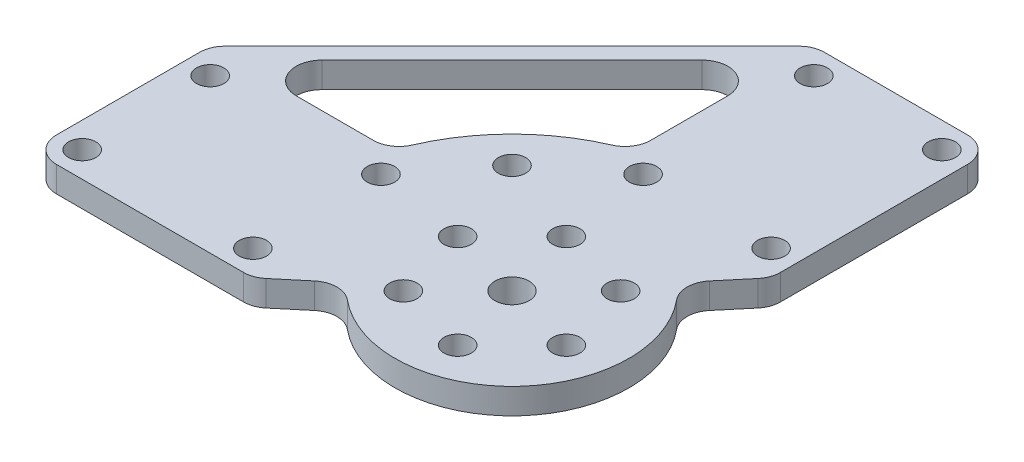
SolidWorks part; units mm, degrees
material "6061-T6 (SS)"
ref_plane "Front Plane" through (0, 0, 0) normal (0, 0, 1) x (1, 0, 0)
ref_plane "Top Plane" through (0, 0, 0) normal (0, 1, 0) x (1, 0, 0)
ref_plane "Right Plane" through (0, 0, 0) normal (1, 0, 0) x (0, 0, -1)
sketch "Sketch1" plane through (0, 0, 0) normal (0, 1, 0) x (1, 0, 0)
  line L0 (-14.5, -32) -> (14.5, -32) construction
  line L1 (10.85, 19.5) -> (-4.15, 19.5)
  line L2 (10.85, 19.5) -> (10.85, 39.5)
  line L3 (10.85, 39.5) -> (-4.15, 39.5)
  line L4 (-4.15, 19.5) -> (-4.15, 39.5)
  line L5 (10.85, 19.5) -> (-4.15, 39.5) construction
  line L6 (10.85, 39.5) -> (-4.15, 19.5) construction
  line L7 (-19.5, -10.85) -> (-39.5, -10.85)
  line L8 (-19.5, -10.85) -> (-19.5, 4.15)
  line L9 (-19.5, 4.15) -> (-39.5, 4.15)
  line L10 (-39.5, -10.85) -> (-39.5, 4.15)
  line L11 (-19.5, -10.85) -> (-39.5, 4.15) construction
  line L12 (-19.5, 4.15) -> (-39.5, -10.85) construction
  line L13 (20.7, 16) -> (-14, 16)
  line L14 (20.7, 16) -> (20.7, 43)
  line L15 (20.7, 43) -> (-14, 43)
  line L16 (-14, 16) -> (-14, 43)
  line L17 (20.7, 16) -> (-14, 43) construction
  line L18 (20.7, 43) -> (-14, 16) construction
  line L19 (-16, -20.7) -> (-43, -20.7)
  line L20 (-16, -20.7) -> (-16, 14)
  line L21 (-16, 14) -> (-43, 14)
  line L22 (-43, -20.7) -> (-43, 14)
  line L23 (-16, -20.7) -> (-43, 14) construction
  line L24 (-16, 14) -> (-43, -20.7) construction
  line L25 (10, -37) -> (-10, -37)
  line L26 (10, -37) -> (10, -27)
  line L27 (10, -27) -> (-10, -27)
  line L28 (-10, -37) -> (-10, -27)
  line L29 (10, -37) -> (-10, -27) construction
  line L30 (10, -27) -> (-10, -37) construction
  line L31 (37, -10) -> (27, -10)
  line L32 (37, -10) -> (37, 10)
  line L33 (37, 10) -> (27, 10)
  line L34 (27, -10) -> (27, 10)
  line L35 (37, -10) -> (27, 10) construction
  line L36 (37, 10) -> (27, -10) construction
  line L37 (32, 14.5) -> (32, -14.5) construction
  circle A0 centre (0, 0) radius 2
  circle A1 centre (0, 0) radius 9
  circle A2 centre (0, 0) radius 12.7
  point P3 (3.35, 29.5)
  point P8 (-29.5, -3.35)
  point P15 (0, -32)
  point P16 (-29.5, -3.35)
  point P17 (3.35, 29.5)
  point P30 (32, 0)
  point P38 (0, -32)
  point P41 (32, 0)
  dimension "D1" = 4
  dimension "D4" = 18
  dimension "D11" = 25.4
  dimension "D2" = 20
  dimension "D3" = 15
  dimension "D5" = 34.7
  dimension "D6" = 27
  dimension "D7" = 2
  dimension "D8" = 2
  dimension "D9" = 16
  dimension "D10" = 16
  dimension "D12" = 32
  dimension "D13" = 10
  dimension "D14" = 20
  dimension "D15" = 32
  dimension "D16" = 4.5
sketch "Sketch2" plane through (0, 0, 0) normal (0, 1, 0) x (1, 0, 0)
  line L3 (-16.5, -13.85) -> (-42.5, -13.85)
  line L4 (-42.5, -13.85) -> (-42.5, 7.15)
  line L5 (-42.5, 7.15) -> (-24.825, 24.825)
  line L6 (-19.5, -10.85) -> (-39.5, -10.85) construction
  line L9 (-39.5, -10.85) -> (-39.5, 4.15) construction
  line L10 (-19.5, -10.85) -> (-19.5, 4.15) construction
  line L12 (-19.5, 4.15) -> (-39.5, 4.15) construction
  line L16 (-16.5, -13.85) -> (-16.5, -29.1277)
  line L22 (16.9749, -34.4749) -> (25.7249, -25.7249)
  line L29 (25.7249, -25.7249) -> (-24.825, 24.825)
  line L39 (12, -27) -> (12, -39)
  line L40 (12, -39) -> (-12, -39)
  line L41 (-12, -39) -> (-12, -27)
  line L42 (12, -34.4495) -> (12, -39)
  line L43 (12, -39) -> (-12, -39)
  line L44 (-12, -39) -> (-12, -34.4495)
  arc A0 (-16.5, -29.1277) -> (-12, -34.4495) centre (-14.5, -32) ccw
  arc A2 (12, -34.4495) -> (16.9749, -34.4749) centre (14.5, -32) ccw
  dimension "D1" = 7
  dimension "D2" = 3
  dimension "D3" = 45
  dimension "D4" = 2
  dimension "D5" = 3
  dimension "D6" = 3
  dimension "D8" = 3
extrude "Boss-Extrude1" add sketch "Sketch2" along normal blind 3
mirror "Mirror5" about plane through (25.7249, 3, 25.7249) normal (-0.7071, 0, 0.7071) of bodies 101
hole_wizard "M3 Clearance Hole1" positions "Sketch3" profile "Sketch4" hole size "M3" standard "ANSI Metric" end condition up to next
sketch "Sketch3" plane through (0, 3, 0) normal (0, 1, 0) x (1, 0, 0)
  point P0 (-39.5, 4.15)
  point P3 (-19.5, 4.15)
  point P6 (-19.5, -10.85)
  point P9 (-39.5, -10.85)
  point P12 (-4.15, 19.5)
  point P15 (-4.15, 39.5)
  point P18 (10.85, 39.5)
  point P21 (10.85, 19.5)
sketch "Sketch4" plane through (-39.5, 3, -4.15) normal (1, 0, 0) x (0, 0, 1)
  line L0 (0, 0) -> (0, 3)
  line L1 (0, 3) -> (1.6, 3)
  line L2 (1.6, 3) -> (1.6, 0)
  line L5 (1.6, 0) -> (0, 0)
  line L11 (0, -6.35) -> (0, 107.95) construction
  dimension "Thru Hole Dia." = 3.2
  dimension "Thru Hole Depth" = 3
hole_wizard "M3 Clearance Hole2" positions "Sketch5" profile "Sketch6" hole size "M3" standard "ANSI Metric" end condition up to next
sketch "Sketch5" plane through (0, 3, 0) normal (0, 1, 0) x (1, 0, 0)
  line L4 (-8.6933, 2.3294) -> (-2.3294, 8.6933) construction
  line L5 (0, 0) -> (-5.5114, 5.5114) construction
  line L7 (-1000, 0) -> (49000, 0) construction
  circle A0 centre (0, 0) radius 9 construction
  point P23 (-2.3294, 8.6933)
  point P46 (6.364, 6.364)
  point P47 (8.6933, -2.3294)
  point P48 (2.3294, -8.6933)
  point P49 (-6.364, -6.364)
  point P50 (-8.6933, 2.3294)
  dimension "D1" = 45
  dimension "D2" = 6
sketch "Sketch6" plane through (-2.3294, 3, -8.6933) normal (1, 0, 0) x (0, 0, 1)
  line L0 (0, 0) -> (0, 3)
  line L1 (0, 3) -> (1.6, 3)
  line L2 (1.6, 3) -> (1.6, 0)
  line L5 (1.6, 0) -> (0, 0)
  line L11 (0, -6.35) -> (0, 107.95) construction
  dimension "Thru Hole Dia." = 3.2
  dimension "Thru Hole Depth" = 3
hole_wizard "Ø4.0 (4) Diameter Hole1" positions "Sketch7" profile "Sketch8" hole size "Ø4.0" standard "ANSI Metric" end condition up to next
sketch "Sketch7" plane through (0, 3, 0) normal (0, 1, 0) x (1, 0, 0)
  point P0 (0, 0)
sketch "Sketch8" plane through (0, 3, 0) normal (1, 0, 0) x (0, 0, 1)
  line L0 (0, 0) -> (0, 3)
  line L1 (0, 3) -> (2, 3)
  line L2 (2, 3) -> (2, 0)
  line L5 (2, 0) -> (0, 0)
  line L11 (0, -6.35) -> (0, 107.95) construction
  dimension "Thru Hole Dia." = 4
  dimension "Thru Hole Depth" = 3
sketch "Sketch13" plane through (0, 3, 0) normal (0, 1, 0) x (1, 0, 0)
  line L0 (-39.6716, 7.15) -> (-21.3337, 7.15)
  line L1 (0, 0) -> (-24.825, 24.825) construction
  line L2 (-7.15, 42.5) -> (-42.5, 7.15) construction
  line L4 (-23.4108, 23.4108) -> (-15.9099, 15.9099)
  line L5 (-5.7358, 41.0858) -> (-41.0858, 5.7358)
  line L6 (-23.4108, 23.4108) -> (-39.6716, 7.15)
  circle A2 centre (0, 0) radius 22.5 construction
  circle A3 centre (-19.5, 4.15) radius 1.6 construction
  arc A4 (-21.3337, 7.15) -> (-15.9099, 15.9099) centre (0, 0) cw
  dimension "D1" = 45
  dimension "D2" = 3
  dimension "D3" = 2
extrude "Cut-Extrude3" cut sketch "Sketch13" against normal up to surface (3 mm away) contours L0 A4 L4 L6 up to face at (0, 0, 2)
mirror "Mirror6" about plane through (0, -28.7929, 0) normal (-0.7071, 0, 0.7071) of "Cut-Extrude3"
fillet "Fillet5" radius 3 4 edges at (-7.15, 1.5, -39.6716) (-7.15, 1.5, -21.3337) (-21.3337, 1.5, -7.15) (-39.6716, 1.5, -7.15)
hole_wizard "M3 Clearance Hole3" positions "Sketch14" profile "Sketch15" hole size "M3" standard "ANSI Metric" end condition up to next
sketch "Sketch14" plane through (0, 3, 0) normal (0, 1, 0) x (1, 0, 0)
  line L0 (-12.7279, 12.7279) -> (0, 0) construction
  line L2 (-12.2713, 34.5503) -> (-34.5503, 12.2713) construction
  circle A2 centre (-12.7279, 12.7279) radius 3
  point P0 (-12.7279, 12.7279)
  dimension "D1" = 6
  dimension "D2" = 18
sketch "Sketch15" plane through (-12.7279, 3, -12.7279) normal (1, 0, 0) x (0, 0, 1)
  line L0 (0, 0) -> (0, 3)
  line L1 (0, 3) -> (1.6, 3)
  line L2 (1.6, 3) -> (1.6, 0)
  line L5 (1.6, 0) -> (0, 0)
  line L11 (0, -6.35) -> (0, 107.95) construction
  dimension "Thru Hole Dia." = 3.2
  dimension "Thru Hole Depth" = 3
sketch "Sketch16" plane through (0, 3, 0) normal (0, 1, 0) x (1, 0, 0)
  line L0 (-16.5, -13.85) -> (-10.4933, -8.808)
  line L1 (13.85, 16.5) -> (8.808, 10.4933)
  line L16 (16.9749, -34.4749) -> (34.4749, -16.9749)
  line L17 (34.4495, -12) -> (39, -12)
  line L18 (39, -12) -> (39, 12)
  line L19 (39, 12) -> (34.4495, 12)
  line L20 (29.1277, 16.5) -> (13.85, 16.5)
  line L21 (13.85, 16.5) -> (13.85, 42.5)
  line L22 (13.85, 42.5) -> (-7.15, 42.5)
  line L23 (-7.15, 42.5) -> (-42.5, 7.15)
  line L24 (-42.5, 7.15) -> (-42.5, -13.85)
  line L25 (-42.5, -13.85) -> (-16.5, -13.85)
  line L26 (-16.5, -13.85) -> (-16.5, -29.1277)
  line L27 (-12, -34.4495) -> (-12, -39)
  line L28 (-12, -39) -> (12, -39)
  line L29 (12, -39) -> (12, -34.4495)
  line L30 (16.9749, -34.4749) -> (34.4749, -16.9749)
  line L31 (34.4495, -12) -> (39, -12)
  line L32 (39, -12) -> (39, 12)
  line L33 (39, 12) -> (34.4495, 12)
  line L34 (29.1277, 16.5) -> (13.85, 16.5)
  line L40 (-16.5, -13.85) -> (-16.5, -29.1277)
  line L41 (-12, -34.4495) -> (-12, -39)
  line L42 (-12, -39) -> (12, -39)
  line L43 (12, -39) -> (12, -34.4495)
  arc A0 (-10.4933, -8.808) -> (8.808, 10.4933) centre (0, 0) ccw
  arc A5 (34.4749, -16.9749) -> (34.4495, -12) centre (32, -14.5) ccw
  arc A6 (34.4495, 12) -> (29.1277, 16.5) centre (32, 14.5) ccw
  arc A7 (-16.5, -29.1277) -> (-12, -34.4495) centre (-14.5, -32) ccw
  arc A8 (12, -34.4495) -> (16.9749, -34.4749) centre (14.5, -32) ccw
  arc A9 (34.4749, -16.9749) -> (34.4495, -12) centre (32, -14.5) ccw
  arc A10 (34.4495, 12) -> (29.1277, 16.5) centre (32, 14.5) ccw
  arc A11 (-16.5, -29.1277) -> (-12, -34.4495) centre (-14.5, -32) ccw
  arc A12 (12, -34.4495) -> (16.9749, -34.4749) centre (14.5, -32) ccw
  dimension "D1" = 27.4
  dimension "D2" = 0
extrude "Cut-Extrude4" cut sketch "Sketch16" against normal up to surface (3 mm away) up to face at (-12.7279, 0, -11.1279)
fillet "Fillet6" radius 3 8 edges at (-42.5, 1.5, 13.85) (-42.5, 1.5, -7.15) (-7.15, 1.5, -42.5) (13.85, 1.5, -42.5) (13.85, 1.5, -16.5) (8.808, 1.5, -10.4933) (-10.4933, 1.5, 8.808) (-16.5, 1.5, 13.85)
